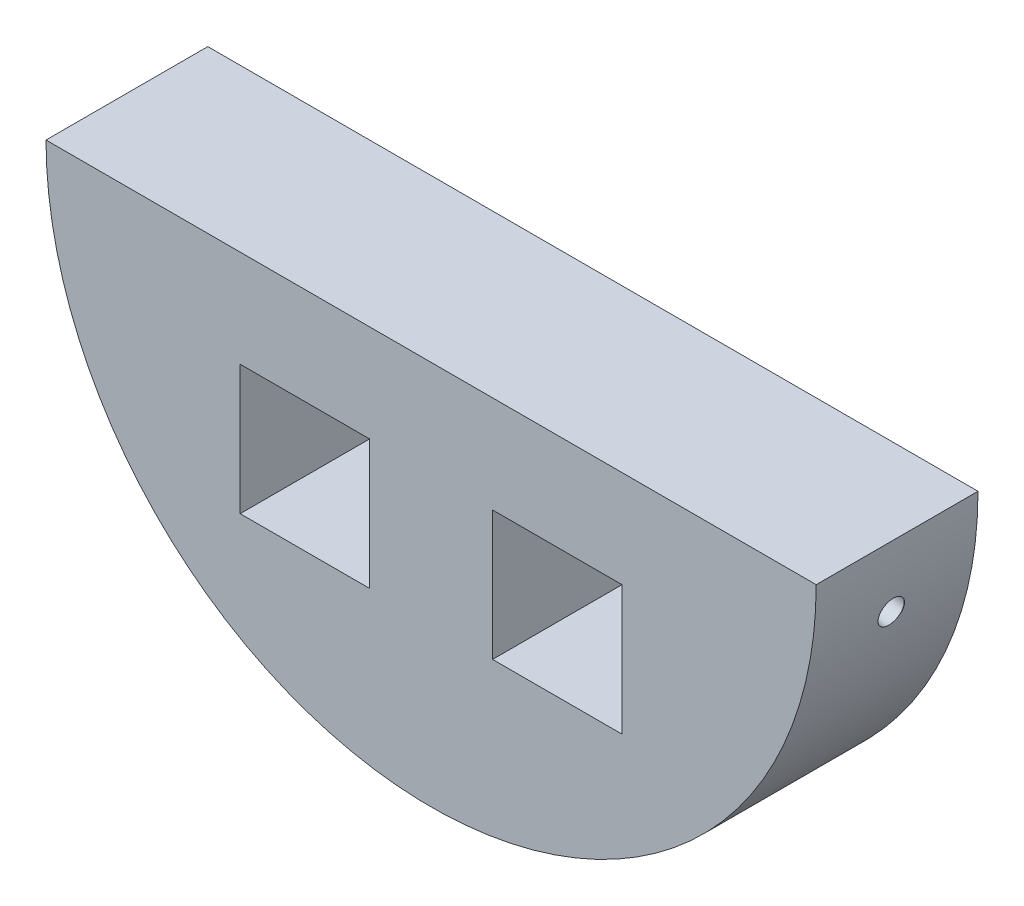
SolidWorks part; units mm, degrees
ref_plane "Front Plane" through (0, 0, 0) normal (0, 0, 1) x (1, 0, 0)
ref_plane "Top Plane" through (0, 0, 0) normal (0, 1, 0) x (1, 0, 0)
ref_plane "Right Plane" through (0, 0, 0) normal (1, 0, 0) x (0, 0, -1)
sketch "Sketch1" plane through (0, 0, 0) normal (0, 0, 1) x (1, 0, 0)
  line L0 (-119, 0) -> (0, 0)
  line L3 (-50, -35) -> (-30, -35)
  line L4 (-50, -35) -> (-50, -15)
  line L5 (-50, -15) -> (-30, -15)
  line L6 (-30, -35) -> (-30, -15)
  line L7 (-89, -35) -> (-69, -35)
  line L8 (-89, -35) -> (-89, -15)
  line L9 (-89, -15) -> (-69, -15)
  line L10 (-69, -35) -> (-69, -15)
  arc A1 (-119, 0) -> (0, 0) centre (-59.5, 0) ccw
  dimension "D1" = 30
  dimension "D7" = 59.5
  dimension "D2" = 15
  dimension "D3" = 30
  dimension "D4" = 20
extrude "Boss-Extrude1" add sketch "Sketch1" along normal blind 25
hole_wizard "Ø4.0mm Dowel Hole2" positions "3DSketch2" profile "Sketch4" hole size "Ø4.0" standard "ANSI Metric"
sketch3d "3DSketch2"
  line L2 (0, 0, 25) -> (0, 0, 0) construction
  line L4 (0, 0, 25) -> (0, 0, 0) construction
  line L5 (0, 0, 12.5) -> (-0.9039, -10.3321, 12.5) construction
  line L8 (-59.5, 0, 0) -> (-59.5, 0, 25) construction
  line L9 (0, 0, 0) -> (-119, 0, 0) construction
  line L10 (0, 0, 25) -> (-119, 0, 25) construction
  line L12 (-59.5, 0, 12.5) -> (-0.9039, -10.3321, 12.5) construction
  line L16 (-59.5, 0, 12.5) -> (0, 0, 12.5) construction
  point P0 (-0.9039, -10.3321, 12.5)
  point P16 (-0.9039, -10.3321, 12.5)
  point P23 (-0.9039, -10.3321, 12.5)
  point P25 (-0.9039, -10.3321, 12.5)
  dimension "D1" = 10
sketch "Sketch4" plane through (-0.9039, -10.3321, 12.5) normal (0, 0, 1) x (0.1736, 0.9848, 0)
  line L0 (0, 0) -> (0, 11.2017)
  line L1 (0, 11.2017) -> (2, 10)
  line L2 (2, 10) -> (2, 0.025)
  line L3 (2, 0.025) -> (2.025, 0)
  line L5 (2.025, 0) -> (0, 0)
  line L6 (-2, 0.025) -> (-2.025, 0) construction
  line L10 (0, 11.2017) -> (-2, 10) construction
  line L11 (0, -6.35) -> (0, 107.95) construction
  dimension "Hole Dia." = 4
  dimension "Hole Depth" = 10
  dimension "Near C'Sink Dia." = 4.05
  dimension "Near C'Sink Angle" = 90
  dimension "Drill Angle" = 118
pattern_circular "CirPattern1" count 5 every 40 about axis through (-59.5, 0, 0) along (0, 0, 1) of "Ø4.0mm Dowel Hole2"
